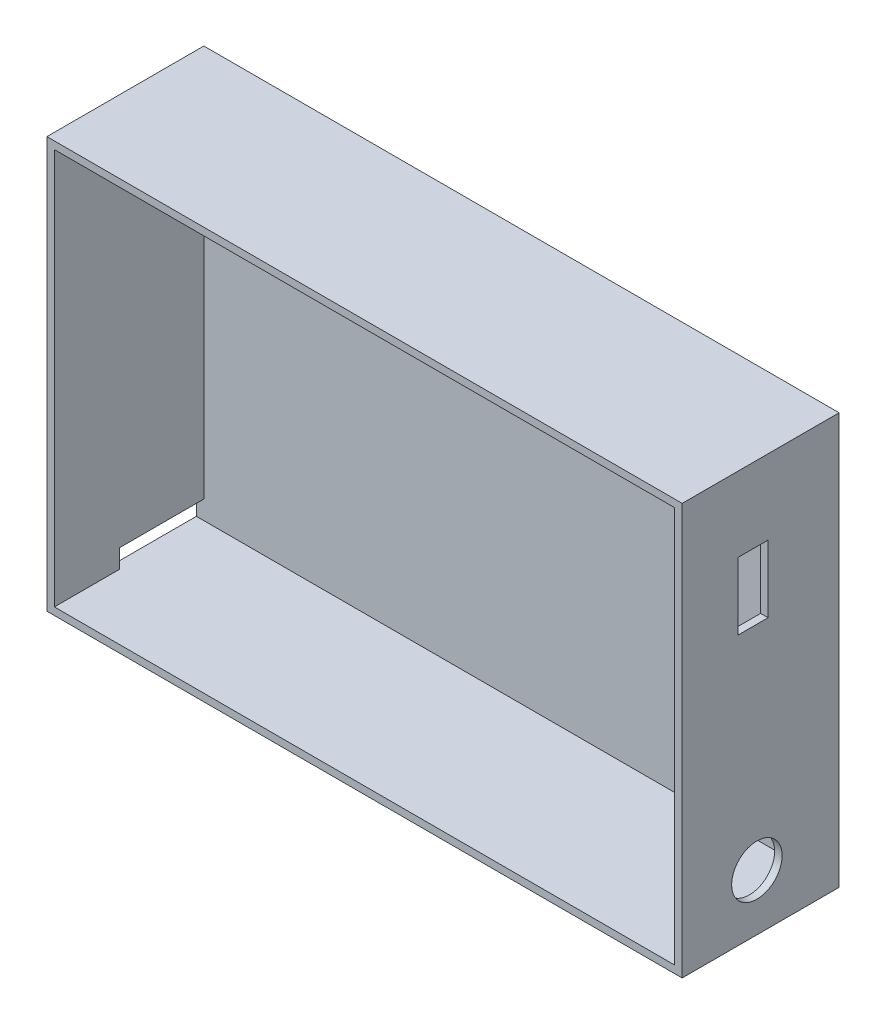
SolidWorks part; units mm, degrees
ref_plane "Front Plane" through (0, 0, 0) normal (0, 0, 1) x (1, 0, 0)
ref_plane "Top Plane" through (0, 0, 0) normal (0, 1, 0) x (1, 0, 0)
ref_plane "Right Plane" through (0, 0, 0) normal (1, 0, 0) x (0, 0, -1)
sketch "Sketch1" plane through (0, 0, 0) normal (0, 0, 1) x (1, 0, 0)
  line L1 (-85, 55) -> (85, 55)
  line L2 (-85, 55) -> (-85, -55)
  line L3 (-85, -55) -> (85, -55)
  line L4 (85, 55) -> (85, -55)
  line L5 (-85, 55) -> (85, -55) construction
  line L6 (-85, -55) -> (85, 55) construction
  point P0 (0, 0)
  dimension "D1" = 170
  dimension "D2" = 110
extrude "Boss-Extrude1" add sketch "Sketch1" along normal blind 2
sketch "Sketch2" plane through (0, 0, 2) normal (0, 0, 1) x (1, 0, 0)
  line L0 (-83, 53) -> (-83, -53)
  line L1 (-85, 55) -> (85, 55)
  line L2 (-85, 55) -> (-85, -55)
  line L3 (-85, -55) -> (85, -55)
  line L4 (85, 55) -> (85, -55)
  line L5 (-83, -53) -> (83, -53)
  line L6 (83, 53) -> (83, -53)
  line L7 (-83, 53) -> (83, 53)
  dimension "D1" = 2
extrude "Boss-Extrude2" add sketch "Sketch2" along normal blind 40
sketch "Sketch3" plane through (85, 0, 0) normal (1, 0, 0) x (0, 0, -1)
  line L0 (0, -55) -> (0, 55) construction
  line L1 (-27, 35) -> (-19, 35)
  line L2 (-27, 35) -> (-27, 17)
  line L3 (-27, 17) -> (-19, 17)
  line L4 (-19, 35) -> (-19, 17)
  line L5 (-27, 35) -> (-19, 17) construction
  line L6 (-27, 17) -> (-19, 35) construction
  line L7 (-42, -55) -> (-42, 55) construction
  line L8 (-42, 55) -> (0, 55) construction
  line L9 (-42, -55) -> (0, -55) construction
  circle A0 centre (-22, -39.9912) radius 6.75
  point P0 (-23, 26)
  point P7 (-23, 17)
  point P8 (-19, 26)
  point P11 (-27, 26)
  point P14 (-23, 35)
  dimension "D3" = 13.5
  dimension "D6" = 22
  dimension "D9" = 20
  dimension "D10" = 15.0088
  dimension "D1" = 18
  dimension "D2" = 8
  dimension "D4" = 57
  dimension "D5" = 19
  dimension "D7" = 15
  dimension "D8" = 20
extrude "Cut-Extrude1" cut sketch "Sketch3" against normal blind 2
sketch "Sketch4" plane through (-85, 0, 0) normal (-1, 0, 0) x (0, 0, 1)
  line L0 (0, 55) -> (0, -55) construction
  line L1 (2, -48) -> (24.6081, -48)
  line L2 (2, -48) -> (2, -53)
  line L3 (2, -53) -> (24.6081, -53)
  line L4 (24.6081, -48) -> (24.6081, -53)
  line L5 (42, -55) -> (0, -55) construction
  point P4 (2, -50.5)
  point P9 (13.304, -53)
  dimension "D1" = 2
  dimension "D2" = 2
  dimension "D3" = 5
  dimension "D5" = 22.6081
extrude "Cut-Extrude2" cut sketch "Sketch4" against normal blind 2
